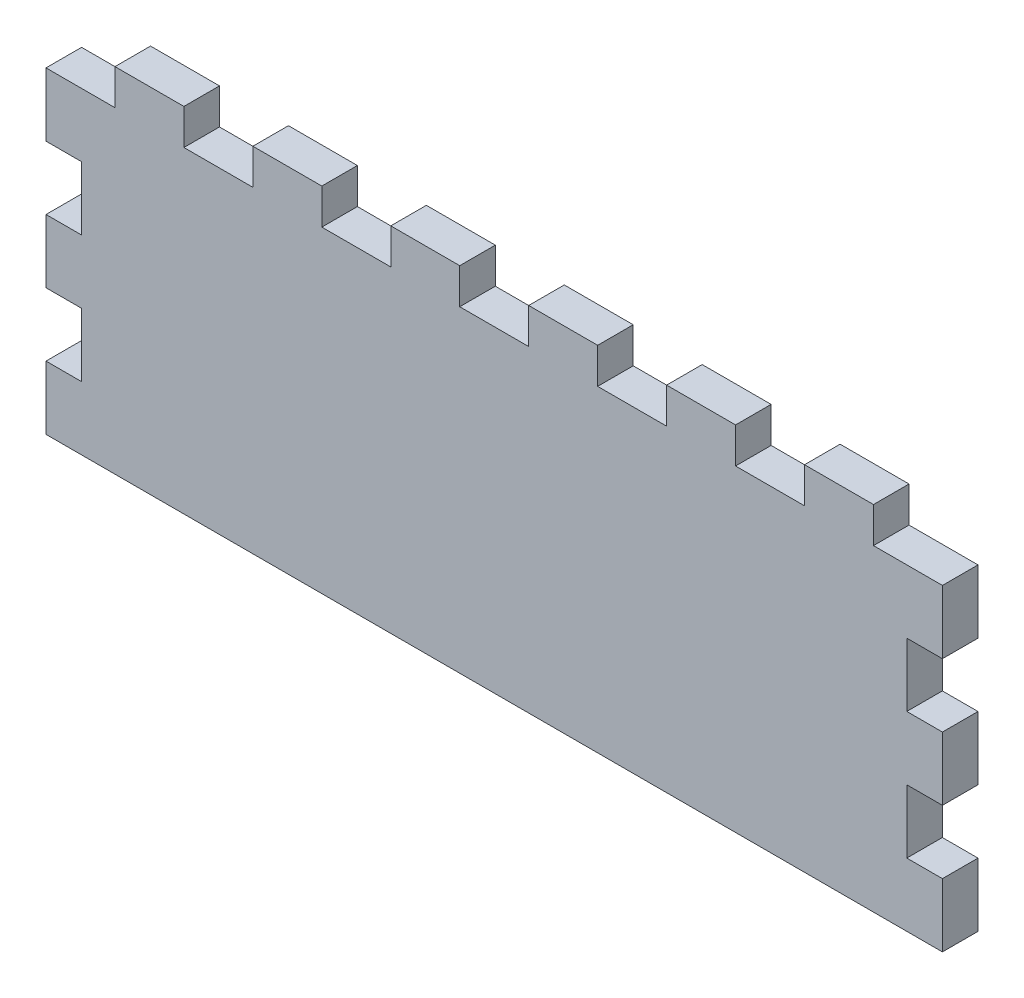
SolidWorks part; units mm, degrees
material "Acrylic (Medium-high impact)"
ref_plane "Front Plane" through (0, 0, 0) normal (0, 0, 1) x (1, 0, 0)
ref_plane "Top Plane" through (0, 0, 0) normal (0, 1, 0) x (1, 0, 0)
ref_plane "Right Plane" through (0, 0, 0) normal (1, 0, 0) x (0, 0, -1)
sketch "Sketch1" plane through (0, 0, 0) normal (0, 0, 1) x (1, 0, 0)
  line L1 (-40, -40) -> (40, -40)
  line L2 (-40, -40) -> (-40, 40)
  line L3 (-40, 40) -> (40, 40)
  line L4 (40, -40) -> (40, 40)
  line L5 (-40, -40) -> (40, 40) construction
  line L6 (-40, 40) -> (40, -40) construction
  point P0 (0, 0)
  dimension "D1" = 80
extrude "Boss-Extrude1" add sketch "Sketch1" along normal mid plane 3.175
sketch "Sketch2" plane through (0, 0, 1.5875) normal (0, 0, 1) x (1, 0, 0)
  line L0 (33.8462, -36.825) -> (40, -36.825)
  line L1 (40, 40) -> (-40, 40) construction
  line L2 (0, 0) -> (50000, 0) construction
  line L3 (40, -40) -> (40, 40) construction
  line L7 (-40, 36.825) -> (-33.8462, 36.825)
  line L8 (-33.8462, 36.825) -> (-33.8462, 40)
  line L9 (-33.8462, 40) -> (-27.6923, 40)
  line L10 (-21.5385, 40) -> (-15.3846, 40)
  line L11 (-21.5385, 36.825) -> (-21.5385, 40)
  line L12 (-27.6923, 36.825) -> (-21.5385, 36.825)
  line L13 (-27.6923, 40) -> (-27.6923, 36.825)
  line L14 (-9.2308, 40) -> (-3.0769, 40)
  line L15 (-9.2308, 36.825) -> (-9.2308, 40)
  line L16 (-15.3846, 36.825) -> (-9.2308, 36.825)
  line L17 (-15.3846, 40) -> (-15.3846, 36.825)
  line L18 (3.0769, 40) -> (9.2308, 40)
  line L19 (3.0769, 36.825) -> (3.0769, 40)
  line L20 (-3.0769, 36.825) -> (3.0769, 36.825)
  line L21 (-3.0769, 40) -> (-3.0769, 36.825)
  line L22 (15.3846, 40) -> (21.5385, 40)
  line L23 (15.3846, 36.825) -> (15.3846, 40)
  line L24 (9.2308, 36.825) -> (15.3846, 36.825)
  line L25 (9.2308, 40) -> (9.2308, 36.825)
  line L28 (21.5385, 36.825) -> (27.6923, 36.825)
  line L29 (21.5385, 40) -> (21.5385, 36.825)
  line L30 (27.6923, 40) -> (33.8462, 40) [skipped]
  line L57 (-40, 40) -> (-40, -40) construction
  line L58 (27.6923, 36.825) -> (27.6923, 40) [skipped]
  line L61 (27.6923, 36.825) -> (27.6923, 40)
  line L62 (27.6923, 40) -> (33.8462, 40)
  line L63 (33.8462, 40) -> (33.8462, 36.825)
  line L64 (33.8462, 36.825) -> (40, 36.825)
  line L65 (33.8462, -40) -> (33.8462, -36.825)
  line L66 (27.6923, -40) -> (33.8462, -40)
  line L67 (27.6923, -36.825) -> (27.6923, -40)
  line L68 (21.5385, -40) -> (21.5385, -36.825)
  line L69 (21.5385, -36.825) -> (27.6923, -36.825)
  line L70 (9.2308, -40) -> (9.2308, -36.825)
  line L71 (9.2308, -36.825) -> (15.3846, -36.825)
  line L72 (15.3846, -36.825) -> (15.3846, -40)
  line L73 (15.3846, -40) -> (21.5385, -40)
  line L74 (-3.0769, -40) -> (-3.0769, -36.825)
  line L75 (-3.0769, -36.825) -> (3.0769, -36.825)
  line L76 (3.0769, -36.825) -> (3.0769, -40)
  line L77 (3.0769, -40) -> (9.2308, -40)
  line L78 (-15.3846, -40) -> (-15.3846, -36.825)
  line L79 (-15.3846, -36.825) -> (-9.2308, -36.825)
  line L80 (-9.2308, -36.825) -> (-9.2308, -40)
  line L81 (-9.2308, -40) -> (-3.0769, -40)
  line L82 (-27.6923, -40) -> (-27.6923, -36.825)
  line L83 (-27.6923, -36.825) -> (-21.5385, -36.825)
  line L84 (-21.5385, -36.825) -> (-21.5385, -40)
  line L85 (-21.5385, -40) -> (-15.3846, -40)
  line L86 (-33.8462, -40) -> (-27.6923, -40)
  line L87 (-33.8462, -36.825) -> (-33.8462, -40)
  line L88 (-40, -36.825) -> (-33.8462, -36.825)
  line L91 (-40, 36.825) -> (-40, 31.1596)
  line L92 (-40, 31.1596) -> (-36.82, 31.1596)
  line L93 (-36.82, 31.1596) -> (-36.82, 25.4942)
  line L94 (-36.82, 25.4942) -> (-40, 25.4942)
  line L95 (-40, 25.4942) -> (-40, 19.8288)
  line L96 (-40, 19.8288) -> (-36.82, 19.8288)
  line L97 (-36.82, 19.8288) -> (-36.82, 14.1635)
  line L98 (-36.82, 14.1635) -> (-40, 14.1635)
  line L99 (-40, 14.1635) -> (-40, 8.4981)
  line L100 (-40, 8.4981) -> (-36.82, 8.4981)
  line L101 (-36.82, 8.4981) -> (-36.82, 2.8327)
  line L102 (-36.82, 2.8327) -> (-40, 2.8327)
  line L103 (-40, 2.8327) -> (-40, -2.8327)
  line L104 (-40, -2.8327) -> (-36.82, -2.8327)
  line L105 (-36.82, -2.8327) -> (-36.82, -8.4981)
  line L106 (-36.82, -8.4981) -> (-40, -8.4981)
  line L107 (-40, -8.4981) -> (-40, -14.1635)
  line L108 (-40, -14.1635) -> (-36.82, -14.1635)
  line L109 (-36.82, -14.1635) -> (-36.82, -19.8288)
  line L110 (-36.82, -19.8288) -> (-40, -19.8288)
  line L111 (-40, -19.8288) -> (-40, -25.4942)
  line L112 (-40, -25.4942) -> (-36.82, -25.4942)
  line L113 (-36.82, -25.4942) -> (-36.82, -31.1596)
  line L114 (-36.82, -31.1596) -> (-40, -31.1596)
  line L115 (-40, -31.1596) -> (-40, -36.825)
  line L116 (0, 0) -> (0, 50000) construction
  line L117 (40, -31.1596) -> (40, -36.825)
  line L118 (36.82, -31.1596) -> (40, -31.1596)
  line L119 (36.82, -25.4942) -> (36.82, -31.1596)
  line L120 (40, 36.825) -> (40, 31.1596)
  line L121 (40, -25.4942) -> (36.82, -25.4942)
  line L122 (40, -19.8288) -> (40, -25.4942)
  line L123 (36.82, -19.8288) -> (40, -19.8288)
  line L124 (36.82, -14.1635) -> (36.82, -19.8288)
  line L125 (40, -14.1635) -> (36.82, -14.1635)
  line L126 (40, -8.4981) -> (40, -14.1635)
  line L127 (36.82, -8.4981) -> (40, -8.4981)
  line L128 (36.82, -2.8327) -> (36.82, -8.4981)
  line L129 (40, -2.8327) -> (36.82, -2.8327)
  line L130 (40, 2.8327) -> (40, -2.8327)
  line L131 (36.82, 2.8327) -> (40, 2.8327)
  line L132 (36.82, 8.4981) -> (36.82, 2.8327)
  line L133 (40, 8.4981) -> (36.82, 8.4981)
  line L134 (40, 14.1635) -> (40, 8.4981)
  line L135 (36.82, 14.1635) -> (40, 14.1635)
  line L136 (36.82, 19.8288) -> (36.82, 14.1635)
  line L137 (40, 19.8288) -> (36.82, 19.8288)
  line L138 (40, 25.4942) -> (40, 19.8288)
  line L139 (36.82, 25.4942) -> (40, 25.4942)
  line L140 (36.82, 31.1596) -> (36.82, 25.4942)
  line L141 (40, 31.1596) -> (36.82, 31.1596)
  point P10 (40, 0)
  point P82 (0, 40)
  dimension "D1" = 3.175
  dimension "D3" = 3.18
  dimension "D5" = 6
  dimension "D6" = 6
extrude "Cut-Extrude2" cut sketch "Sketch2" against normal blind 10 flip side to cut
sketch "Sketch3" plane through (0, 0, 1.5875) normal (0, 0, 1) x (1, 0, 0)
  line L0 (-40, -31.1596) -> (-40, -36.825) construction
  line L1 (-40, -40) -> (40, -40)
  line L2 (-40, -40) -> (-40, 8.4981)
  line L3 (-40, 8.4981) -> (40, 8.4981)
  line L4 (40, -40) -> (40, 8.4981)
  line L5 (27.6923, -40) -> (33.8462, -40) construction
  line L6 (-40, 8.4981) -> (-36.82, 8.4981) construction
  dimension "D2" = 80
extrude "Cut-Extrude3" cut sketch "Sketch3" against normal through all
